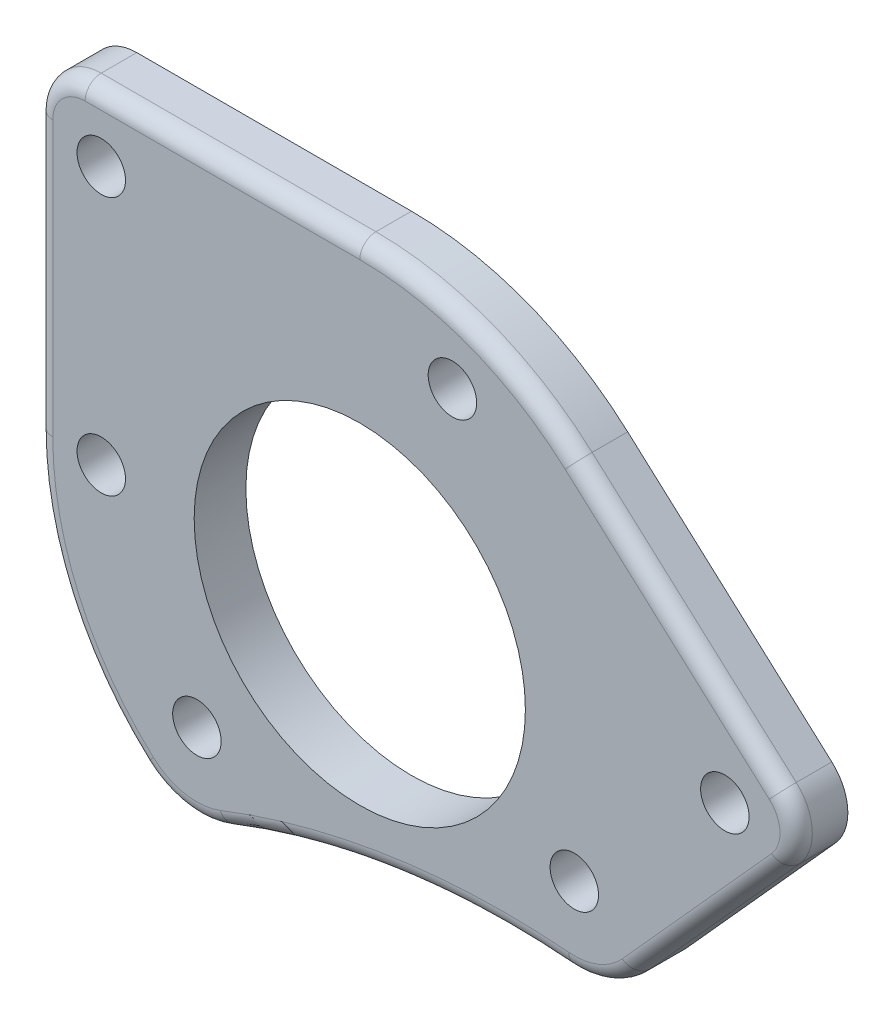
SolidWorks part; units mm, degrees
material "尼龙 101"
ref_plane "前视基准面" through (0, 0, 0) normal (0, 0, 1) x (1, 0, 0)
ref_plane "上视基准面" through (0, 0, 0) normal (0, 1, 0) x (1, 0, 0)
ref_plane "右视基准面" through (0, 0, 0) normal (1, 0, 0) x (0, 0, -1)
sketch "草图1" plane through (0, 0, 0) normal (0, 0, 1) x (1, 0, 0)
  line L0 (4.334, 74.8629) -> (16.9675, 63.4877) construction
  line L1 (17.1895, 59.2508) -> (7.945, 48.9837) construction
  line L2 (-29.0486, 60) -> (-29.0486, 77) construction
  line L3 (-26.0486, 80) -> (-9.0486, 80) construction
  line L4 (4.334, 74.8629) -> (16.9675, 63.4877)
  line L5 (17.1895, 59.2508) -> (7.945, 48.9837)
  line L6 (-29.0486, 60) -> (-29.0486, 77)
  line L7 (-26.0486, 80) -> (-9.0486, 80)
  arc A0 (4.334, 74.8629) -> (-9.0486, 80) centre (-9.0486, 60) ccw construction
  arc A1 (17.1895, 59.2508) -> (16.9675, 63.4877) centre (14.9601, 61.2582) ccw construction
  arc A2 (3.8264, 47.3456) -> (7.945, 48.9837) centre (4.2292, 52.3294) ccw construction
  arc A3 (3.8264, 47.3456) -> (-17.3064, 44.235) centre (0, 0) ccw construction
  arc A4 (-22.488, 45.1885) -> (-17.3064, 44.235) centre (-19.1282, 48.8913) ccw construction
  arc A5 (-29.0486, 60) -> (-22.488, 45.1885) centre (-9.0486, 60) ccw construction
  arc A6 (-26.0486, 80) -> (-29.0486, 77) centre (-26.0486, 77) ccw construction
  arc A7 (4.334, 74.8629) -> (-9.0486, 80) centre (-9.0486, 60) ccw
  arc A8 (17.1895, 59.2508) -> (16.9675, 63.4877) centre (14.9601, 61.2582) ccw
  arc A9 (3.8264, 47.3456) -> (7.945, 48.9837) centre (4.2292, 52.3294) ccw
  arc A10 (3.8264, 47.3456) -> (-17.3064, 44.235) centre (0, 0) ccw
  arc A11 (-22.488, 45.1885) -> (-17.3064, 44.235) centre (-19.1282, 48.8913) ccw
  arc A12 (-29.0486, 60) -> (-22.488, 45.1885) centre (-9.0486, 60) ccw
  arc A13 (-26.0486, 80) -> (-29.0486, 77) centre (-26.0486, 77) ccw
  circle A16 centre (-9.0486, 60) radius 10.25
  circle A17 centre (-25.0486, 76) radius 1.5
  circle A18 centre (-25.0486, 76) radius 1.5
  circle A19 centre (-3.3147, 74.9373) radius 1.5
  circle A20 centre (-3.3147, 74.9373) radius 1.5
  circle A21 centre (-25.0486, 60) radius 1.5
  circle A22 centre (-25.0486, 60) radius 1.5
  circle A23 centre (-19.1282, 48.8913) radius 1.5
  circle A24 centre (-19.1282, 48.8913) radius 1.5
  circle A25 centre (4.2292, 52.3294) radius 1.5
  circle A26 centre (4.2292, 52.3294) radius 1.5
  circle A27 centre (13.5478, 61.1842) radius 1.5
  circle A28 centre (13.5478, 61.1842) radius 1.5
  dimension "D2" = 0
  dimension "D3" = 0
  dimension "D4" = 0
  dimension "D5" = 0
  dimension "D6" = 0
  dimension "D7" = 0
extrude "凸台-拉伸1" add sketch "草图1" along normal blind 3.2
fillet "圆角1" radius 1
